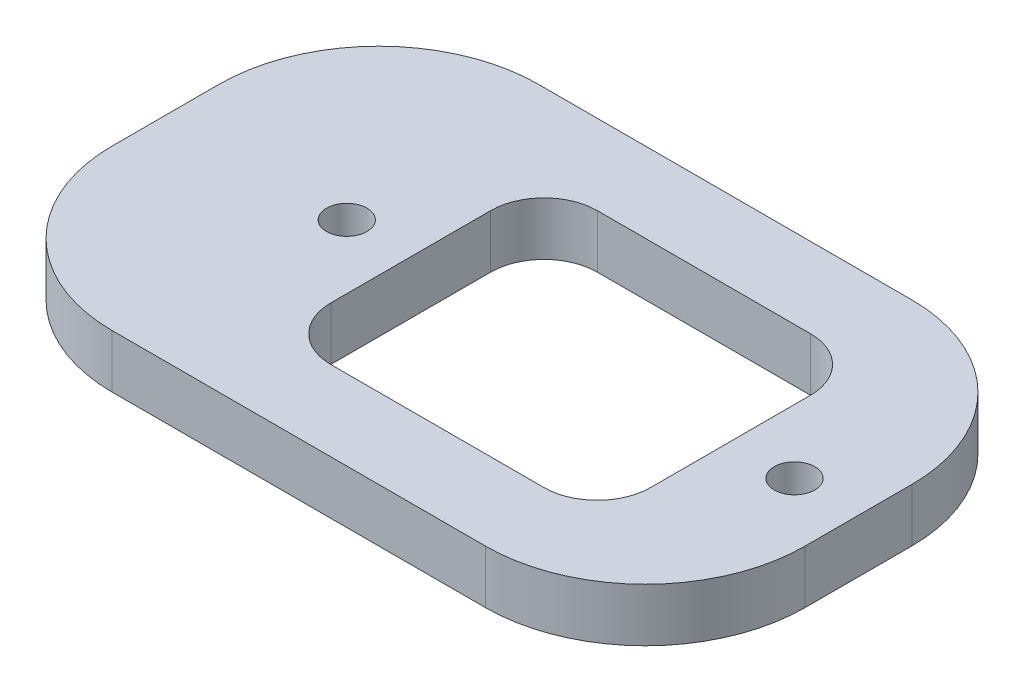
SolidWorks part; units mm, degrees
ref_plane "Front Plane" through (0, 0, 0) normal (0, 0, 1) x (1, 0, 0)
ref_plane "Top Plane" through (0, 0, 0) normal (0, 1, 0) x (1, 0, 0)
ref_plane "Right Plane" through (0, 0, 0) normal (1, 0, 0) x (0, 0, -1)
sketch "Sketch1" plane through (0, 0, 0) normal (0, 1, 0) x (1, 0, 0)
  line L0 (-20.32, -12.7) -> (-20.32, -25.4)
  line L1 (-49.53, -22.225) -> (-49.53, -15.875) construction
  line L2 (13.97, 6.35) -> (-30.48, 6.35)
  line L3 (33.02, -12.7) -> (33.02, -25.4)
  line L4 (13.97, -44.45) -> (-30.48, -44.45)
  line L5 (17.78, -12.7) -> (17.78, -25.4)
  line L8 (-49.53, -12.7) -> (-49.53, -25.4)
  line L9 (33.02, -22.225) -> (33.02, -15.875) construction
  line L16 (-20.32, -12.7) -> (-20.32, -9.525)
  line L17 (-13.97, -3.175) -> (11.43, -3.175)
  line L18 (17.78, -12.7) -> (17.78, -9.525)
  line L20 (-20.32, -25.4) -> (-20.32, -28.575)
  line L21 (-13.97, -34.925) -> (11.43, -34.925)
  line L22 (17.78, -25.4) -> (17.78, -28.575)
  arc A0 (17.78, -9.525) -> (11.43, -3.175) centre (11.43, -9.525) ccw
  arc A1 (33.02, -12.7) -> (13.97, 6.35) centre (13.97, -12.7) ccw
  arc A2 (33.02, -25.4) -> (13.97, -44.45) centre (13.97, -25.4) cw
  arc A3 (-49.53, -25.4) -> (-30.48, -44.45) centre (-30.48, -25.4) ccw
  arc A4 (-30.48, 6.35) -> (-49.53, -12.7) centre (-30.48, -12.7) ccw
  arc A5 (11.43, -34.925) -> (17.78, -28.575) centre (11.43, -28.575) ccw
  arc A6 (-20.32, -28.575) -> (-13.97, -34.925) centre (-13.97, -28.575) ccw
  arc A7 (-20.32, -9.525) -> (-13.97, -3.175) centre (-13.97, -9.525) cw
  point P29 (0, 0)
  point P38 (-49.53, -44.45)
  point P41 (-49.53, 6.35)
  dimension "D5" = 38.1
  dimension "D3" = 19.05
  dimension "D6" = 6.35
  dimension "D7" = 9.525
  dimension "D1" = 50.8
  dimension "D2" = 25.4
  dimension "D4" = 31.75
extrude "Boss-Extrude1" add sketch "Sketch1" along normal blind 6.35
hole_wizard "CSK for #10 Flat Head Machine Screw1" positions "Sketch3" profile "Sketch4" countersink size "#10" standard "ANSI Inch" end condition through all
sketch "Sketch3" plane through (0, 0, 0) normal (0, -1, 0) x (-1, 0, 0)
  line L7 (-13.97, 6.35) -> (30.48, 6.35) construction
  line L8 (-33.02, -25.4) -> (-33.02, -12.7) construction
  line L9 (-33.02, -25.4) -> (-33.02, -12.7) construction
  point P0 (27.94, -19.05)
  point P24 (-25.4, -19.05)
  point P33 (-33.02, -19.05)
  point P37 (-33.02, -19.05)
  dimension "D1" = 53.34
  dimension "D2" = 25.4
  dimension "D3" = 7.62
  dimension "D4" = 7.62
sketch "Sketch4" plane through (-27.94, 0, 19.05) normal (1, 0, 0) x (0, 0, -1)
  line L0 (0, 0) -> (0, 6.35)
  line L1 (0, 6.35) -> (2.413, 6.35)
  line L2 (2.413, 6.35) -> (2.413, 2.7028)
  line L3 (2.413, 2.7028) -> (4.7625, 0)
  line L5 (4.7625, 0) -> (0, 0)
  line L6 (-2.413, 2.7028) -> (-4.7625, 0) construction
  line L11 (0, -6.35) -> (0, 107.95) construction
  dimension "Thru Hole Dia." = 4.826
  dimension "Thru Hole Depth" = 6.35
  dimension "Near C'Sink Dia." = 9.525
  dimension "Near C'Sink Angle" = 82
